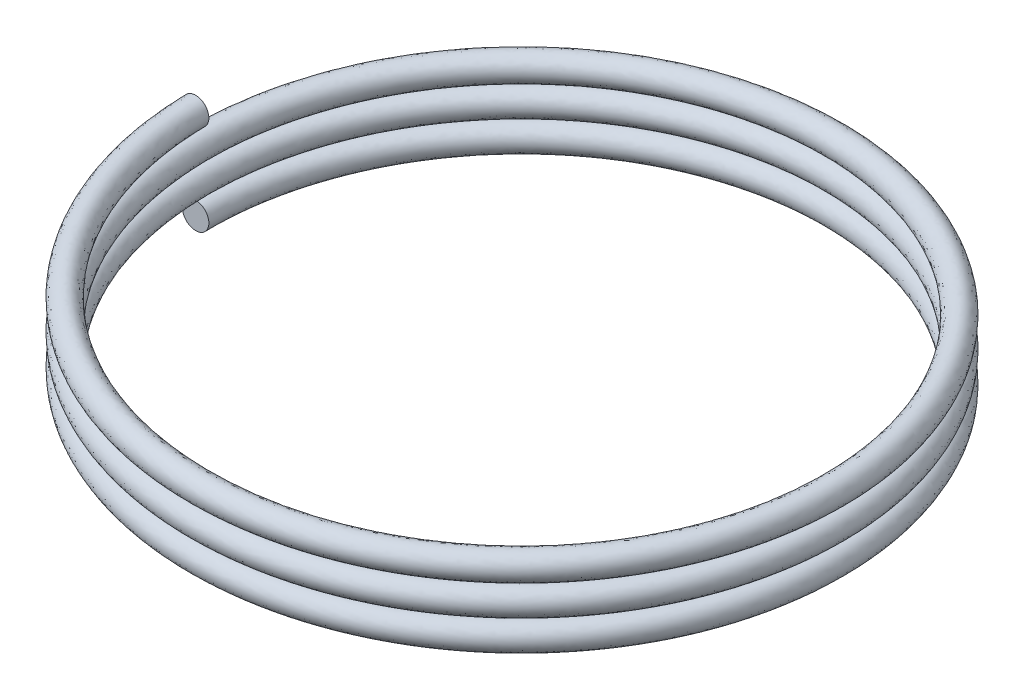
SolidWorks part; units mm, degrees
material "AISI Type 316L stainless steel"
ref_plane "Front Plane" through (0, 0, 0) normal (0, 0, 1) x (1, 0, 0)
ref_plane "Top Plane" through (0, 0, 0) normal (0, 1, 0) x (1, 0, 0)
ref_plane "Right Plane" through (0, 0, 0) normal (1, 0, 0) x (0, 0, -1)
sketch "Sketch1" plane through (0, 0, 0) normal (0, 1, 0) x (1, 0, 0)
  circle A0 centre (0, 0) radius 30.48
  dimension "D1" = 60.96
curve "Helix/Spiral1" pitch 2.921 height 8.763 turns 3
sketch "Sketch3" plane through (0, 0, 0) normal (0, 0, 1) x (1, 0, 0)
  circle A0 centre (-30.48, 0) radius 1.27
  spline S0 degree 3 poles (-30.48, 0) (-30.48, 0.0399) (-29.7988, 0.1201) (-26.8013, 0.2401) (-22.0267, 0.3601) (-15.7916, 0.4802) (-8.5095, 0.6002) (-0.6631, 0.7202) (7.2272, 0.8403) (14.6383, 0.9603) (21.0788, 1.0804) (26.1217, 1.2004) (29.4326, 1.3205) (30.7921, 1.4405) (30.1098, 1.5605) (27.4312, 1.6806) (22.9337, 1.8006) (16.9157, 1.9207) (9.776, 2.0407) (1.9882, 2.1607) (-5.9315, 2.2808) (-13.4578, 2.4008) (-20.0919, 2.5209) (-25.3938, 2.6409) (-29.012, 2.7609) (-30.7065, 2.881) (-30.3651, 3.001) (-28.0103, 3.1211) (-23.7983, 3.2411) (-18.0084, 3.3612) (-11.0245, 3.4812) (-3.3096, 3.6012) (4.6248, 3.7213) (12.2525, 3.8413) (19.0678, 3.9614) (24.6189, 4.0814) (28.5375, 4.2014) (30.5641, 4.3215) (30.5641, 4.4415) (28.5375, 4.5616) (24.6189, 4.6816) (19.0678, 4.8016) (12.2525, 4.9217) (4.6248, 5.0417) (-3.3096, 5.1618) (-11.0245, 5.2818) (-18.0084, 5.4018) (-23.7983, 5.5219) (-28.0103, 5.6419) (-30.3651, 5.762) (-30.7065, 5.882) (-29.012, 6.0021) (-25.3938, 6.1221) (-20.0919, 6.2421) (-13.4578, 6.3622) (-5.9315, 6.4822) (1.9882, 6.6023) (9.776, 6.7223) (16.9157, 6.8423) (22.9337, 6.9624) (27.4312, 7.0824) (30.1098, 7.2025) (30.7921, 7.3225) (29.4326, 7.4425) (26.1217, 7.5626) (21.0788, 7.6826) (14.6383, 7.8027) (7.2272, 7.9227) (-0.6631, 8.0428) (-8.5095, 8.1628) (-15.7916, 8.2828) (-22.0267, 8.4029) (-26.8013, 8.5229) (-29.7988, 8.6429) (-30.48, 8.7231) (-30.48, 8.763) knots 0 0 0 0 0.013699 0.027397 0.041096 0.054795 0.068493 0.082192 0.09589 0.109589 0.123288 0.136986 0.150685 0.164384 0.178082 0.191781 0.205479 0.219178 0.232877 0.246575 0.260274 0.273973 0.287671 0.30137 0.315068 0.328767 0.342466 0.356164 0.369863 0.383562 0.39726 0.410959 0.424658 0.438356 0.452055 0.465753 0.479452 0.493151 0.506849 0.520548 0.534247 0.547945 0.561644 0.575342 0.589041 0.60274 0.616438 0.630137 0.643836 0.657534 0.671233 0.684932 0.69863 0.712329 0.726027 0.739726 0.753425 0.767123 0.780822 0.794521 0.808219 0.821918 0.835616 0.849315 0.863014 0.876712 0.890411 0.90411 0.917808 0.931507 0.945205 0.958904 0.972603 0.986301 1 1 1 1 construction
  dimension "D1" = 2.54
sweep "Sweep1" add profiles "Sketch3" path "Helix/Spiral1"
sketch "Sketch4" plane through (0, 0, 0) normal (0, 0, 1) x (1, 0, 0)
  circle A0 centre (-30.48, 0) radius 1.27 construction
  point P0 (-31.048, -1.1359)
sketch "Sketch6" plane through (0, 0, 0) normal (0, 0, -1) x (-1, 0, 0)
  circle A0 centre (30.48, 8.763) radius 1.27 construction
  point P0 (30.48, 10.033)
